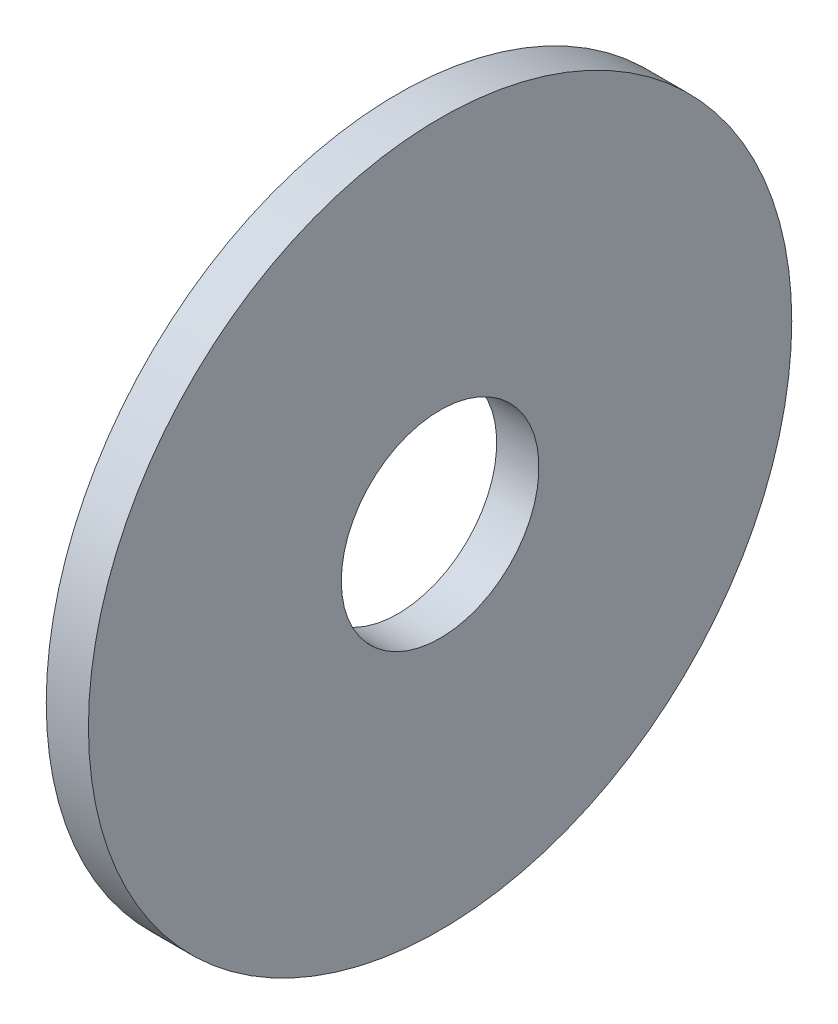
SolidWorks part; units mm, degrees
ref_plane "Front Plane" through (0, 0, 0) normal (0, 0, 1) x (1, 0, 0)
ref_plane "Top Plane" through (0, 0, 0) normal (0, 1, 0) x (1, 0, 0)
ref_plane "Right Plane" through (0, 0, 0) normal (1, 0, 0) x (0, 0, -1)
sketch "Sketch1" plane through (0, 0, 0) normal (1, 0, 0) x (0, 0, -1)
  circle A0 centre (0, 0) radius 12.7
  circle A1 centre (0, 0) radius 3.5687
  dimension "OD" = 25.4
  dimension "ID" = 7.1374
extrude "Boss-Extrude1" add sketch "Sketch1" along normal blind 1.524
